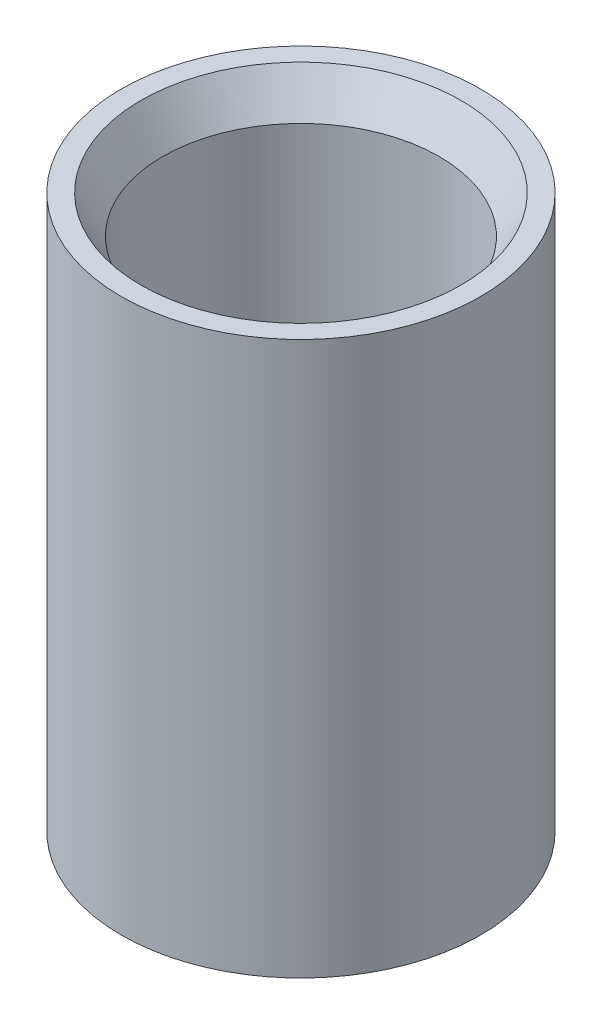
SolidWorks part; units mm, degrees
material "PVC Rigid"
ref_plane "Front Plane" through (0, 0, 0) normal (0, 0, 1) x (1, 0, 0)
ref_plane "Top Plane" through (0, 0, 0) normal (0, 1, 0) x (1, 0, 0)
ref_plane "Right Plane" through (0, 0, 0) normal (1, 0, 0) x (0, 0, -1)
sketch "Sketch1" plane through (0, 0, 0) normal (0, 1, 0) x (1, 0, 0)
  circle A0 centre (0, 0) radius 12.7
  circle A1 centre (0, 0) radius 16.51
  dimension "D1" = 25.4
  dimension "D2" = 33.02
extrude "Boss-Extrude1" add sketch "Sketch1" along normal blind 50.8
chamfer "Chamfer1" distance 2 angle 60 1 edges at (0, 50.8, 12.7)
